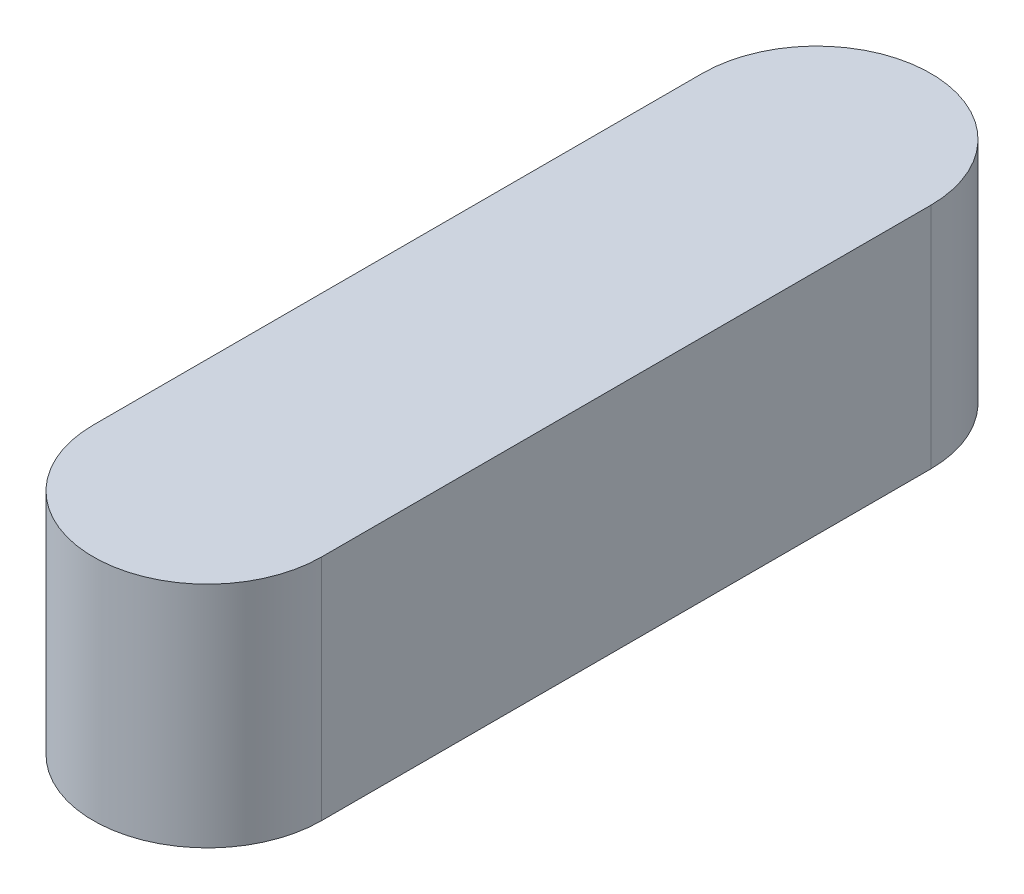
SolidWorks part; units mm, degrees
ref_plane "Front Plane" through (0, 0, 0) normal (0, 0, 1) x (1, 0, 0)
ref_plane "Top Plane" through (0, 0, 0) normal (0, 1, 0) x (1, 0, 0)
ref_plane "Right Plane" through (0, 0, 0) normal (1, 0, 0) x (0, 0, -1)
sketch "Sketch1" plane through (0, 0, 0) normal (0, 0, 1) x (1, 0, 0)
  line L1 (-3, -3) -> (3, -3)
  line L2 (-3, -3) -> (-3, 3)
  line L3 (-3, 3) -> (3, 3)
  line L4 (3, -3) -> (3, 3)
  line L5 (-3, -3) -> (3, 3) construction
  line L6 (-3, 3) -> (3, -3) construction
  point P0 (0, 0)
  dimension "D1" = 6
  dimension "D2" = 6
extrude "Boss-Extrude1" add sketch "Sketch1" along normal mid plane 16
sketch "Sketch2" plane through (0, -3, 0) normal (0, -1, 0) x (1, 0, 0)
  line L0 (-3, 8) -> (3, 8) construction
  line L1 (-3, -8) -> (3, -8) construction
  line L2 (-3, 8) -> (3, 8)
  line L3 (-3, -8) -> (3, -8)
  arc A0 (-3, 8) -> (3, 8) centre (0, 8) cw
  arc A1 (3, -8) -> (-3, -8) centre (0, -8) cw
extrude "Boss-Extrude2" add sketch "Sketch2" against normal up to surface (6 mm away) up to face at (0, 3, 0)
